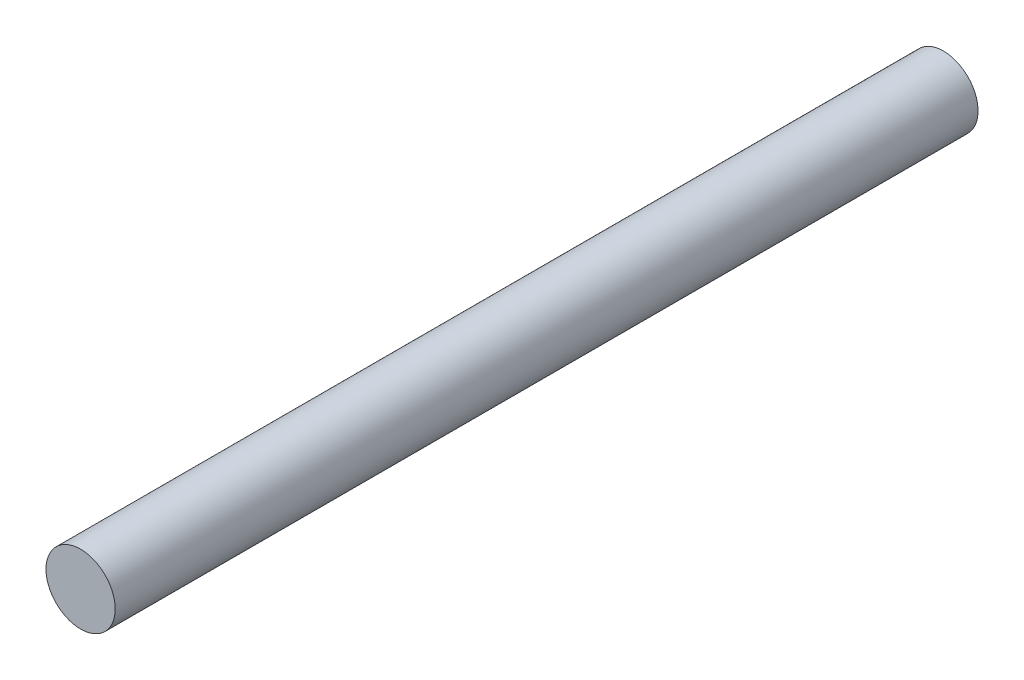
SolidWorks part; units mm, degrees
ref_plane "前视基准面" through (0, 0, 0) normal (0, 0, 1) x (1, 0, 0)
ref_plane "上视基准面" through (0, 0, 0) normal (0, 1, 0) x (1, 0, 0)
ref_plane "右视基准面" through (0, 0, 0) normal (1, 0, 0) x (0, 0, -1)
other "Configuration Table"
sketch "草图1" plane through (0, 0, 0) normal (0, 0, 1) x (1, 0, 0)
  circle A0 centre (0, 0) radius 14.44
  dimension "D1" = 28.88
extrude "凸台-拉伸1" add sketch "草图1" along normal blind 360
